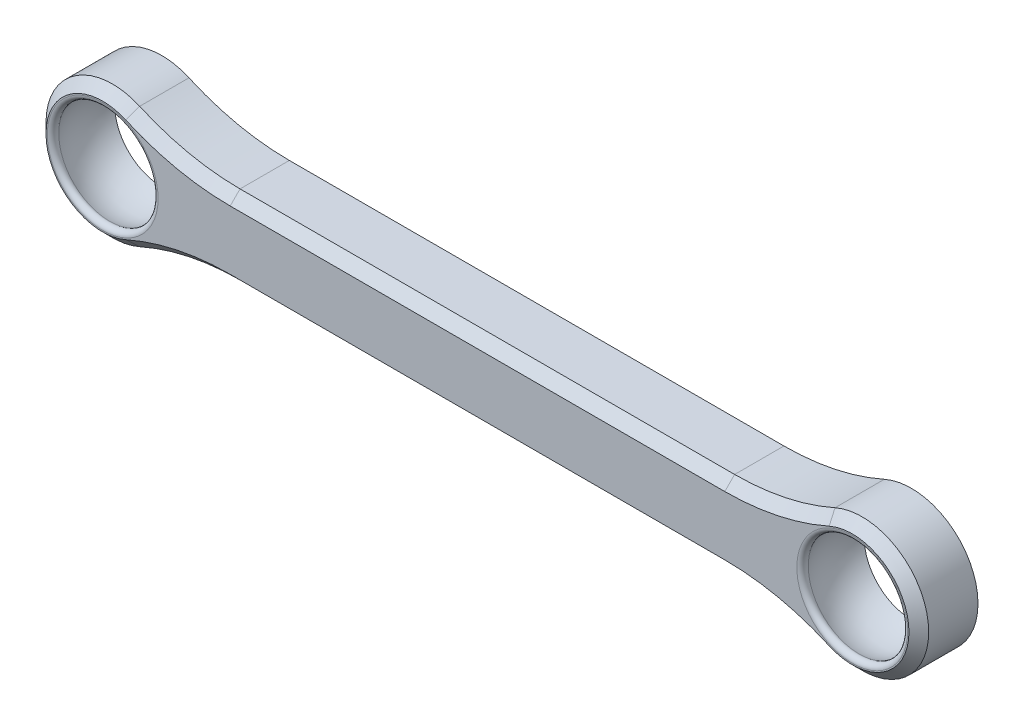
SolidWorks part; units mm, degrees
ref_plane "Front Plane" through (0, 0, 0) normal (0, 0, 1) x (1, 0, 0)
ref_plane "Top Plane" through (0, 0, 0) normal (0, 1, 0) x (1, 0, 0)
ref_plane "Right Plane" through (0, 0, 0) normal (1, 0, 0) x (0, 0, -1)
ref_plane "Plane2" through (0, 0, 0) normal (0, 0, -1) x (-1, 0, 0)
sketch "Sketch7" plane through (0, 0, 0) normal (0, 0, -1) x (-1, 0, 0)
  line L0 (-78.5629, -4) -> (-13.4371, -4)
  line L1 (-13.4371, 4) -> (-78.5629, 4)
  arc A0 (-13.4371, -4) -> (-13.4371, 4) centre (-8, 0) ccw
  arc A1 (-78.5629, 4) -> (-78.5629, -4) centre (-84, 0) ccw
extrude "Boss-Extrude2" add sketch "Sketch7" against normal blind 6 separate body
sketch "Sketch10" plane through (0, 0, 0) normal (0, 1, 0) x (1, 0, 0)
  line L0 (88.7877, 0) -> (84, 0)
  line L1 (84, 0) -> (84, -6)
  line L2 (84, -6) -> (89.6189, -6)
  line L3 (84, 0) -> (84, -6) construction
  arc A0 (89.6189, -6) -> (89.1621, -5.2967) centre (89.6189, -5.5) cw
  arc A1 (89.1621, -5.2967) -> (88.7877, 0) centre (84, -3) ccw
revolve "Cut-Revolve3" cut sketch "Sketch10" angle 360 about L1
sketch "Sketch13" plane through (0, 0, 0) normal (0, 1, 0) x (1, 0, 0)
  line L0 (12.7877, 0) -> (8, 0)
  line L1 (8, 0) -> (8, -6)
  line L2 (8, -6) -> (13.6189, -6)
  line L3 (8, 0) -> (8, -6) construction
  arc A0 (13.6189, -6) -> (13.1621, -5.2967) centre (13.6189, -5.5) cw
  arc A1 (13.1621, -5.2967) -> (12.7877, 0) centre (8, -3) ccw
revolve "Cut-Revolve4" cut sketch "Sketch13" angle 360 about L1
fillet "Fillet2" radius 25 4 edges at (78.5629, 4, 3) (13.4371, -4, 3) (78.5629, -4, 3) (13.4371, 4, 3)
chamfer "Chamfer2" distance 1 angle 45 8 edges at (76.2773, -4.5473, 6) (90.75, 0, 6) (46, -4, 6) (76.2773, 4.5473, 6) (15.7227, -4.5473, 6) (46, 4, 6) (1.25, 0, 6) (15.7227, 4.5473, 6)
